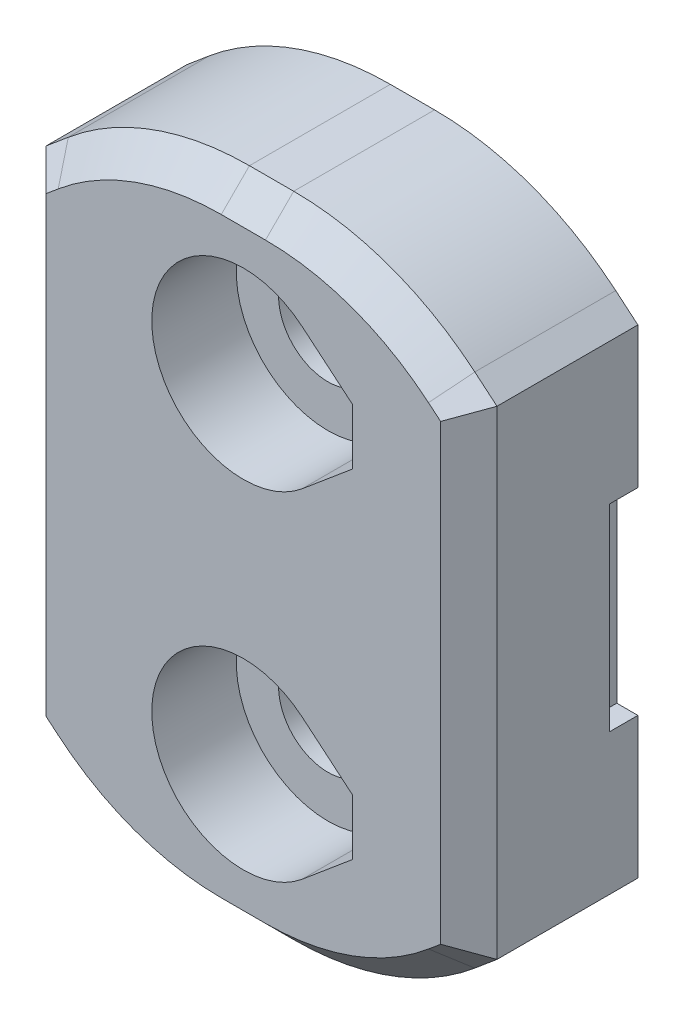
SolidWorks part; units mm, degrees
ref_plane "Alzado" through (0, 0, 0) normal (0, 0, 1) x (1, 0, 0)
ref_plane "Planta" through (0, 0, 0) normal (0, 1, 0) x (1, 0, 0)
ref_plane "Vista lateral" through (0, 0, 0) normal (1, 0, 0) x (0, 0, -1)
sketch "Croquis2" plane through (0, 0, 0) normal (0, 0, -1) x (-1, 0, 0)
  line L0 (-8, 0) -> (-8, 5.5) construction
  line L1 (-16, 23) -> (0, 23)
  line L2 (-16, 0) -> (-16, 23)
  line L3 (-16, 0) -> (0, 0)
  line L4 (0, 23) -> (0, 0)
  line L5 (-8, 5.5) -> (-8, 17.5) construction
  line L6 (-8, 11.5) -> (0, 11.5) construction
  line L7 (-9.9777, 6.125) -> (-9.9777, 4.875)
  line L8 (-9.9777, 4.875) -> (-9.1249, 4.1594)
  line L9 (-9.9777, 6.125) -> (-9.1249, 6.8406)
  line L10 (-9.9777, 18.125) -> (-9.9777, 16.875)
  line L11 (-9.9777, 18.125) -> (-9.1249, 18.8406)
  line L12 (-9.9777, 16.875) -> (-9.1249, 16.1594)
  arc A1 (-9.1249, 16.1594) -> (-9.1249, 18.8406) centre (-8, 17.5) ccw
  arc A3 (-9.1249, 4.1594) -> (-9.1249, 6.8406) centre (-8, 5.5) ccw
  dimension "D5" = 3.5
  dimension "D1" = 16
  dimension "D2" = 23
  dimension "D3" = 12
  dimension "D4" = 1.25
  dimension "D6" = 80
extrude "Saliente-Extruir1" add sketch "Croquis2" along normal blind 6 separate body
sketch "Croquis3" plane through (-8, 0, 0) normal (0, 0, -1) x (-1, 0, 0)
  line L0 (-19.8643, 6.5) -> (-19.8643, 4.5)
  line L1 (-19.8643, 4.5) -> (-18.0891, 3.0104)
  line L2 (-19.8643, 6.5) -> (-18.0891, 7.9896)
  line L3 (-19.8643, 18.5) -> (-18.0891, 19.9896)
  line L4 (-19.8643, 18.5) -> (-19.8643, 16.5)
  line L5 (-19.8643, 16.5) -> (-18.0891, 15.0104)
  arc A0 (-18.0891, 15.0104) -> (-18.0891, 19.9896) centre (-16, 17.5) ccw
  arc A1 (-18.0891, 3.0104) -> (-18.0891, 7.9896) centre (-16, 5.5) ccw
  dimension "D1" = 2
  dimension "D2" = 6.5
  dimension "D3" = 80
  dimension "D4" = 2
  dimension "D5" = 80
extrude "Cortar-Extruir1" cut sketch "Croquis3" along normal blind 3
chamfer "Chaflán2" distance 3 angle 50 4 edges at (16, 23, -3) (16, 0, -3) (0, 0, -3) (0, 23, -3)
fillet "Redondeo1" radius 10 4 edges at (3.5753, 0, -3) (12.4247, 0, -3) (12.4247, 23, -3) (3.5753, 23, -3)
chamfer "Chaflán1" distance 1 angle 45 12 edges at (16, 11.5, 0) (8, 0, 0) (8, 23, 0) (0, 11.5, 0) (0.3935, 2.6698, 0) (3.7948, 0.6031, 0) (15.6065, 2.6698, 0) (12.2052, 0.6031, 0) (15.6065, 20.3302, 0) (12.2052, 22.3969, 0) (0.3935, 20.3302, 0) (3.7948, 22.3969, 0)
sketch "Croquis4" plane through (0, 0, -6) normal (0, 0, -1) x (-1, 0, 0)
  line L0 (-16, 20) -> (-16, 3) construction
  line L1 (-16, 15) -> (0, 15)
  line L2 (-16, 15) -> (-16, 8)
  line L3 (-16, 8) -> (0, 8)
  line L4 (0, 15) -> (0, 8)
  line L5 (0, 3) -> (0, 20) construction
  line L6 (-16, 11.5) -> (-8, 11.5) construction
  line L7 (-8, 17.5) -> (-8, 5.5) construction
  dimension "D1" = 7
extrude "Cortar-Extruir2" cut sketch "Croquis4" against normal blind 1
sketch "Croquis5" plane through (0, 8, 0) normal (0, 1, 0) x (1, 0, 0)
  line L0 (0, 5) -> (0.8391, 6)
  line L1 (1.25, 6) -> (0.8391, 6)
  line L2 (1.25, 6) -> (1.25, 5)
  line L3 (16, 5) -> (0, 5) construction
  line L4 (1.25, 5) -> (0, 5)
  line L6 (16, 6) -> (0, 6) construction
  dimension "D1" = 50
  dimension "D2" = 1.25
extrude "Saliente-Extruir2" add sketch "Croquis5" along normal up to surface (7 mm away) up to face at (8, 15, -5.5)
pattern_linear "MatrizL1" count 8 spacing 2 along (1, 0, 0) of "Saliente-Extruir2"
